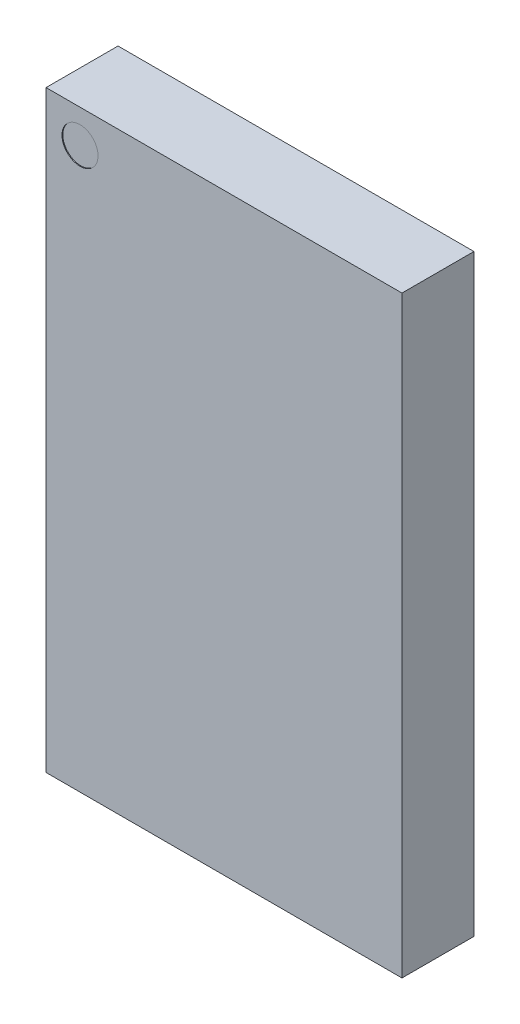
SolidWorks part; units mm, degrees
ref_plane "Front Plane" through (0, 0, 0) normal (0, 0, 1) x (1, 0, 0)
ref_plane "Top Plane" through (0, 0, 0) normal (0, 1, 0) x (1, 0, 0)
ref_plane "Right Plane" through (0, 0, 0) normal (1, 0, 0) x (0, 0, -1)
sketch "Sketch1" plane through (0, 0, 0) normal (0, 0, 1) x (1, 0, 0)
  line L1 (-4.5, -7.5) -> (4.5, -7.5)
  line L2 (-4.5, -7.5) -> (-4.5, 7.5)
  line L3 (-4.5, 7.5) -> (4.5, 7.5)
  line L4 (4.5, -7.5) -> (4.5, 7.5)
  line L5 (-4.5, -7.5) -> (4.5, 7.5) construction
  line L6 (-4.5, 7.5) -> (4.5, -7.5) construction
  point P0 (0, 0)
  dimension "D1" = 15
  dimension "D2" = 9
extrude "Boss-Extrude1" add sketch "Sketch1" along normal blind 1.82 from offset 0.4 contours L4 L3 L2 L1
ref_plane "Plane1" through (0, -6.35, 0) normal (0, -1, 0) x (-1, 0, 0)
sketch "Sketch2" plane through (0, -6.35, 0) normal (0, -1, 0) x (-1, 0, 0)
  line L0 (3.81, -0.53) -> (3.81, 0.1)
  line L2 (4.5, -0.4) -> (-4.5, -0.4) construction
  line L3 (4.5, -2.22) -> (4.5, -0.4) construction
  arc A0 (3.81, 0.1) -> (3.81, -0.53) centre (3.81, -0.215) cw
  dimension "D1" = 0.63
  dimension "D2" = 0.5
  dimension "D3" = 0.69
revolve "Revolve1" add sketch "Sketch2" angle 360 about L0
pattern_linear "LPattern1" count 11 spacing 1.27 along (0, 1, 0) count 7 spacing 1.27 along (1, 0, 0) of "Revolve1"
sketch "Sketch3" plane through (0, 0, 2.22) normal (0, 0, 1) x (1, 0, 0)
  circle A0 centre (-3.6411, 6.6615) radius 0.4556
  point P2 (-3.6411, 6.6615)
extrude "Cut-Extrude1" cut sketch "Sketch3" against normal blind 0.02
